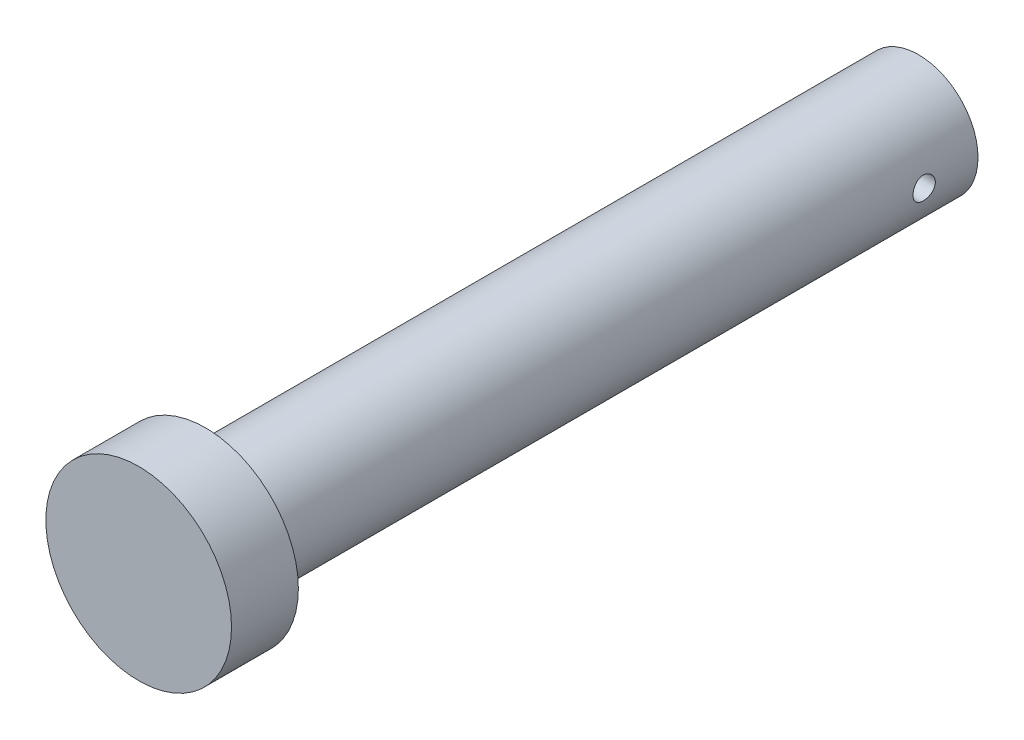
SolidWorks part; units mm, degrees
ref_plane "Front Plane" through (0, 0, 0) normal (0, 0, 1) x (1, 0, 0)
ref_plane "Top Plane" through (0, 0, 0) normal (0, 1, 0) x (1, 0, 0)
ref_plane "Right Plane" through (0, 0, 0) normal (1, 0, 0) x (0, 0, -1)
sketch "Sketch1" plane through (0, 0, 0) normal (0, 0, 1) x (1, 0, 0)
  circle A0 centre (0, 0) radius 12.5
  dimension "D1" = 25
extrude "Boss-Extrude1" add sketch "Sketch1" along normal blind 9
sketch "Sketch2" plane through (0, 0, 0) normal (0, 0, 1) x (1, 0, 0)
  circle A0 centre (0, 0) radius 8
  dimension "D1" = 16
extrude "Boss-Extrude3" add sketch "Sketch2" against normal blind 96
sketch "Sketch3" plane through (0, 0, 0) normal (1, 0, 0) x (0, 0, -1)
  circle A0 centre (88.7552, 0) radius 1.5
  dimension "D1" = 3
extrude "Cut-Extrude1" cut sketch "Sketch3" against normal mid plane 96
